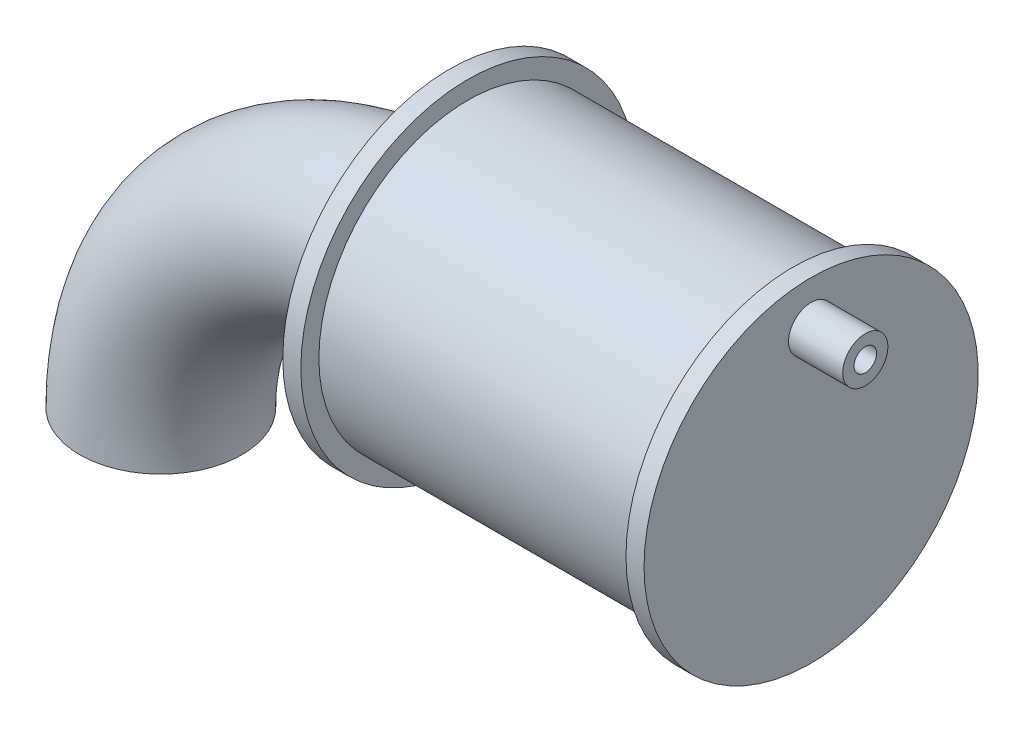
SolidWorks part; units mm, degrees
ref_plane "Face" through (0, 0, 0) normal (0, 0, 1) x (1, 0, 0)
ref_plane "Dessus" through (0, 0, 0) normal (0, 1, 0) x (1, 0, 0)
ref_plane "Droite" through (0, 0, 0) normal (1, 0, 0) x (0, 0, -1)
sketch "Esquisse1" plane through (0, 0, 0) normal (0, 0, 1) x (1, 0, 0)
  line L0 (2, 16.5) -> (38, 16.5)
  line L1 (-25.0815, 0) -> (68.5189, 0) construction
  line L2 (0, 0) -> (0, 18.5)
  line L3 (0, 18.5) -> (2, 18.5)
  line L4 (2, 16.5) -> (2, 18.5)
  line L5 (0, 0) -> (2, 0)
  line L6 (38, 16.5) -> (38, 18.5)
  line L7 (38, 18.5) -> (40, 18.5)
  line L8 (40, 0) -> (40, 18.5)
  line L9 (2, 15.5) -> (38, 15.5)
  line L10 (38, 15.5) -> (38, 0)
  line L11 (2, 15.5) -> (2, 0)
  line L12 (38, 0) -> (40, 0)
  dimension "D1" = 2
  dimension "D2" = 36
  dimension "D3" = 16.5
  dimension "D4" = 2
  dimension "D5" = 2
  dimension "D6" = 1
revolve "Base-Révolution" add sketch "Esquisse1" angle 360 about L1
sketch "Esquisse2" plane through (40, 0, 0) normal (1, 0, 0) x (0, 0, -1)
  circle A0 centre (0, 13.6118) radius 2.5
  dimension "D1" = 5
extrude "Boss.-Extru.1" add sketch "Esquisse2" along normal blind 6
sketch "Esquisse3" plane through (46, 0, 0) normal (1, 0, 0) x (0, 0, -1)
  circle A0 centre (0, 13.6118) radius 1.25
  dimension "D1" = 2.5
extrude "Enlèv. mat.-Extru.1" cut sketch "Esquisse3" against normal blind 14.3
sketch "Esquisse4" plane through (0, 0, 0) normal (-1, 0, 0) x (0, 0, 1)
  circle A0 centre (0, 0) radius 9
  dimension "D1" = 18
extrude "Enlèv. mat.-Extru.2" cut sketch "Esquisse4" against normal blind 5
sketch "Esquisse6" plane through (2, 0, 0) normal (1, 0, 0) x (0, 0, -1)
  circle A0 centre (0, 0) radius 9
  circle A1 centre (0, 0) radius 7
  dimension "D1" = 14
  dimension "D2" = 18
sketch "Esquisse7" plane through (0, 0, 0) normal (0, 0, 1) x (1, 0, 0)
  line L0 (2, 0) -> (-2, 0)
  line L1 (-25.0815, 0) -> (68.5189, 0) construction
  arc A0 (-2, 0) -> (-32, -30) centre (-2, -30) ccw
  dimension "D2" = 60
  dimension "D1" = 4
sweep "Boss.-Balayage1" add profiles "Esquisse6" path "Esquisse7"
